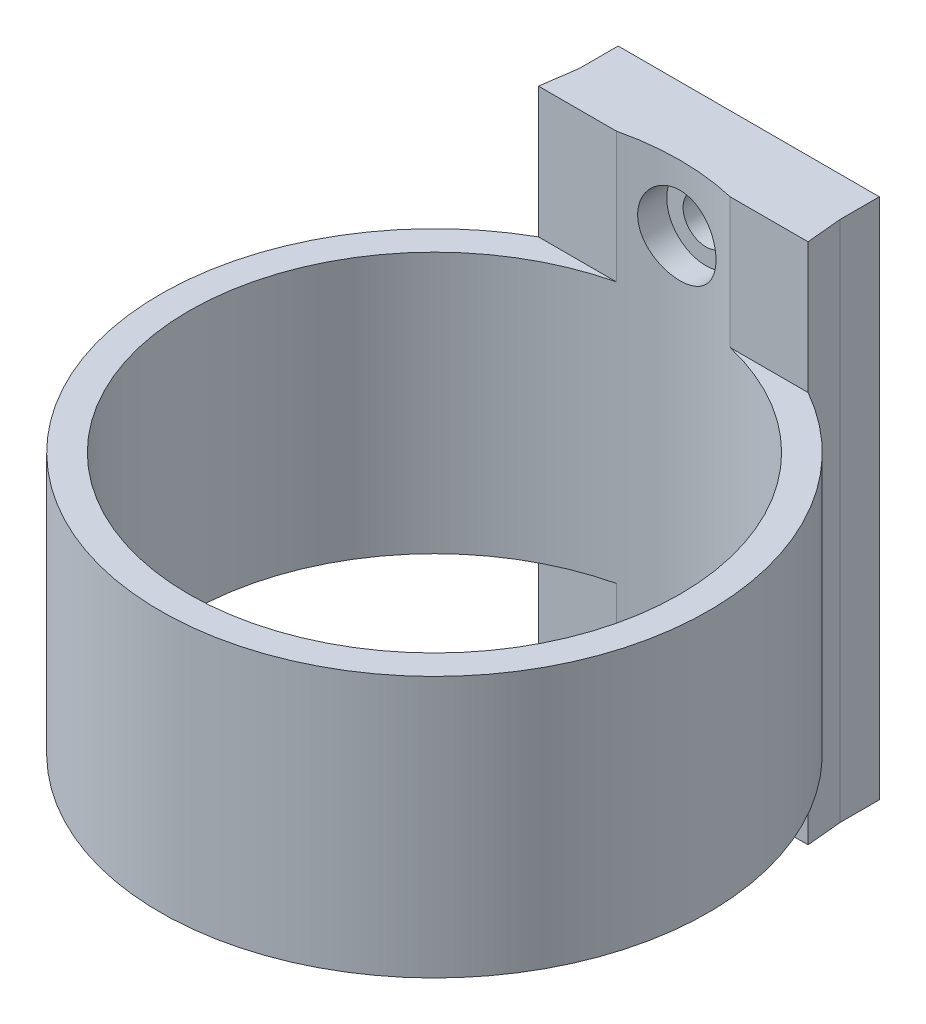
SolidWorks part; units mm, degrees
ref_plane "Front Plane" through (0, 0, 0) normal (0, 0, 1) x (1, 0, 0)
ref_plane "Top Plane" through (0, 0, 0) normal (0, 1, 0) x (1, 0, 0)
ref_plane "Right Plane" through (0, 0, 0) normal (1, 0, 0) x (0, 0, -1)
sketch "Sketch1" plane through (0, 0, 0) normal (0, 1, 0) x (1, 0, 0)
  circle A0 centre (0, 0) radius 18.8
  circle A1 centre (0, 0) radius 21
  dimension "D1" = 37.6
  dimension "D2" = 42
extrude "Boss-Extrude1" add sketch "Sketch1" along normal blind 20 contours A1 A0
ref_plane "Plane1" through (0, 0, -21) normal (0, 0, -1) x (-1, 0, 0)
sketch "Sketch2" plane through (0, 0, -21) normal (0, 0, -1) x (-1, 0, 0)
  line L0 (0, 20) -> (0, 25)
  line L1 (21, 20) -> (-21, 20) construction
  line L2 (-10.0686, -10) -> (9.9314, -10)
  line L5 (-21, 10) -> (21, 10) construction
  line L8 (-21.9857, 10) -> (29.774, 10) construction
  line L13 (-10.0686, -10) -> (-10.0686, 30)
  line L14 (-10.0686, 30) -> (9.9314, 30)
  line L15 (9.9314, -10) -> (9.9314, 30)
  line L16 (-10.0686, -10) -> (9.9314, 30) construction
  line L17 (-10.0686, 30) -> (9.9314, -10) construction
  line L18 (-21, 20) -> (-21, 0) construction
  line L19 (21, 0) -> (21, 20) construction
  circle A0 centre (0, 25) radius 1.75
  circle A1 centre (0, -5) radius 1.75
  point P0 (-0.0686, 10)
  dimension "D3" = 3.5
  dimension "D1" = 20
  dimension "D2" = 40
extrude "Boss-Extrude2" add sketch "Sketch2" along normal blind 3
sketch "Sketch3" plane through (0, 30, 0) normal (0, 1, 0) x (1, 0, 0)
  line L0 (-9.9314, 21) -> (-10.3227, 18.2877)
  line L1 (10.0686, 21) -> (10.3227, 18.2877)
  line L2 (-10.3227, 18.2877) -> (10.3227, 18.2877)
  circle A0 centre (0, 0) radius 21 construction
  line M1 (-9.9314, 21) -> (10.0686, 21)
extrude "Boss-Extrude3" add sketch "Sketch3" against normal up to surface (40 mm away) contours L0 L2 L1 M1 up to face at (0.0686, -10, -22.5)
sketch "Sketch5" plane through (0, 20, 0) normal (0, 1, 0) x (1, 0, 0)
  circle A0 centre (0, 0) radius 18.8
  arc A1 (-4.3587, 18.2877) -> (4.3587, 18.2877) centre (0, 0) ccw construction
sketch "Sketch6" plane through (0, 0, -24) normal (0, 0, -1) x (-1, 0, 0)
  circle A0 centre (0, 25) radius 1.75
  circle A1 centre (0, -5) radius 1.75
extrude "Cut-Extrude2" cut sketch "Sketch6" against normal through all
sketch "Sketch8" plane through (0, 0, -18.2877) normal (0, 0, 1) x (1, 0, 0)
  line L0 (-21, 10) -> (21, 10) construction
  line L1 (-21, 20) -> (-21, 0) construction
  line L2 (21, 0) -> (21, 20) construction
  circle A0 centre (0, 25) radius 3
  circle A1 centre (0, -5) radius 3
  dimension "D1" = 6
extrude "Cut-Extrude3" cut sketch "Sketch8" against normal blind 2.5
extrude "Cut-Extrude4" cut sketch "Sketch5" against normal through all both and the other way through all
